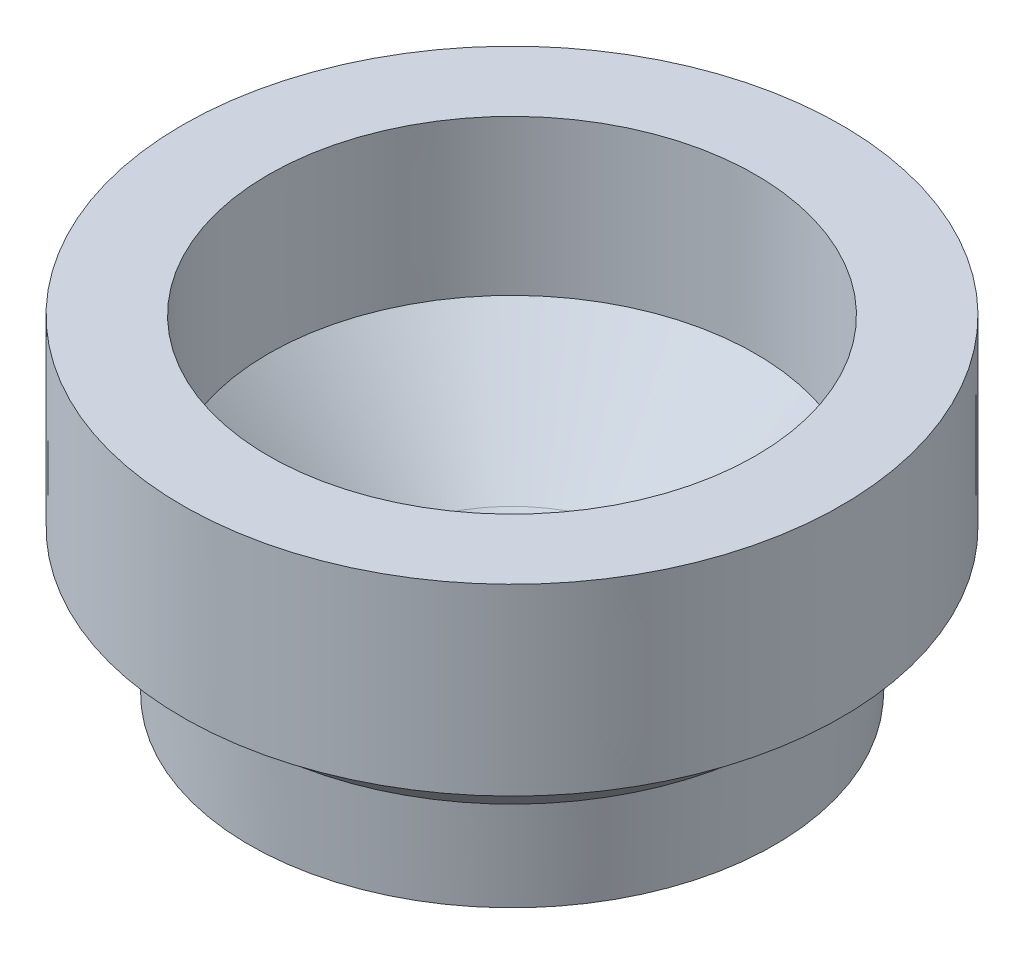
SolidWorks part; units mm, degrees
material "1.4003 (X2CrNi12)"
ref_plane "Ön Düzlem" through (0, 0, 0) normal (0, 0, 1) x (1, 0, 0)
ref_plane "Üst Düzlem" through (0, 0, 0) normal (0, 1, 0) x (1, 0, 0)
ref_plane "Sağ Düzlem" through (0, 0, 0) normal (1, 0, 0) x (0, 0, -1)
sketch "Çizim1" plane through (0, 0, 0) normal (0, 0, 1) x (1, 0, 0)
  line L0 (0.0002, 3.4611) -> (0, 0)
  line L1 (10.2184, 0) -> (12.1903, 1.3904)
  line L2 (12.1903, 1.3904) -> (12.3906, 5.6974)
  line L3 (12.3906, 5.6974) -> (15.0256, 8.0735)
  line L4 (15.0256, 8.0735) -> (15.2941, 8.0736)
  line L5 (15.2941, 8.0736) -> (15.2941, 16.5885)
  line L6 (15.2941, 16.5885) -> (11.3065, 16.5885)
  line L7 (11.3065, 16.5885) -> (11.3065, 9.3923)
  line L8 (11.3065, 9.3923) -> (6.4662, 4.3363)
  line L9 (4.5278, 3.4611) -> (0.0002, 3.4611)
  line L10 (0, 0) -> (10.2184, 0)
  arc A0 (4.5278, 3.4611) -> (6.4662, 4.3363) centre (4.5315, 6.0372) ccw
revolve "Döndür1" add sketch "Çizim1" angle 360 about L0
